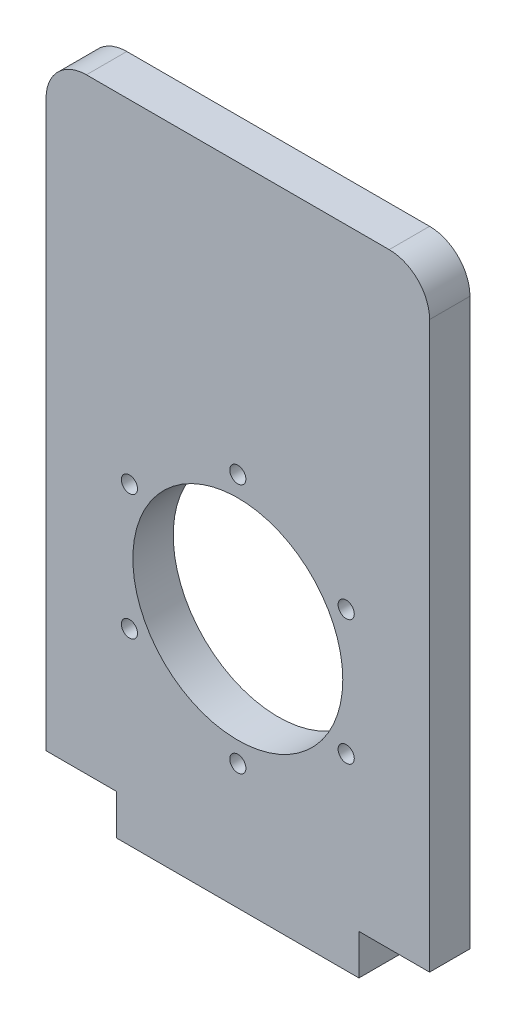
SolidWorks part; units mm, degrees
ref_plane "Front Plane" through (0, 0, 0) normal (0, 0, 1) x (1, 0, 0)
ref_plane "Top Plane" through (0, 0, 0) normal (0, 1, 0) x (1, 0, 0)
ref_plane "Right Plane" through (0, 0, 0) normal (1, 0, 0) x (0, 0, -1)
sketch "Sketch1" plane through (0, 0, 0) normal (0, 0, 1) x (1, 0, 0)
  line L0 (0, 98) -> (0, 0) construction
  line L5 (-47.5, 98) -> (47.5, 98)
  line L6 (-47.5, 98) -> (-47.5, -52)
  line L7 (-47.5, -52) -> (47.5, -52)
  line L8 (47.5, 98) -> (47.5, -52)
  line L9 (30, -52) -> (-30, -52)
  line L10 (30, -52) -> (30, -62)
  line L11 (-30, -52) -> (-30, -62)
  line L12 (30, -62) -> (-30, -62)
  circle A5 centre (0, 0) radius 26
  circle A6 centre (0, 0) radius 31 construction
  circle A7 centre (0, 31) radius 2
  circle A8 centre (26.8468, 15.5) radius 2
  circle A9 centre (26.8468, -15.5) radius 2
  circle A10 centre (0, -31) radius 2
  circle A11 centre (-26.8468, -15.5) radius 2
  circle A12 centre (-26.8468, 15.5) radius 2
  point P0 (0, 0)
  point P11 (0, -52)
  point P12 (0, -52)
  dimension "D1" = 95
  dimension "D4" = 62
  dimension "D6" = 6
  dimension "D3" = 52
  dimension "D5" = 4
  dimension "D2" = 150
  dimension "D7" = 98
  dimension "D8" = 60
  dimension "D9" = 10
extrude "Boss-Extrude1" add sketch "Sketch1" along normal blind 10 contours L8 L5 L6 L7 A12 A11 A10 A9 A8 A7 A5 | L12 L10 L7 L11
fillet "Fillet1" radius 10 2 edges at (47.5, 98, 5) (-47.5, 98, 5)
